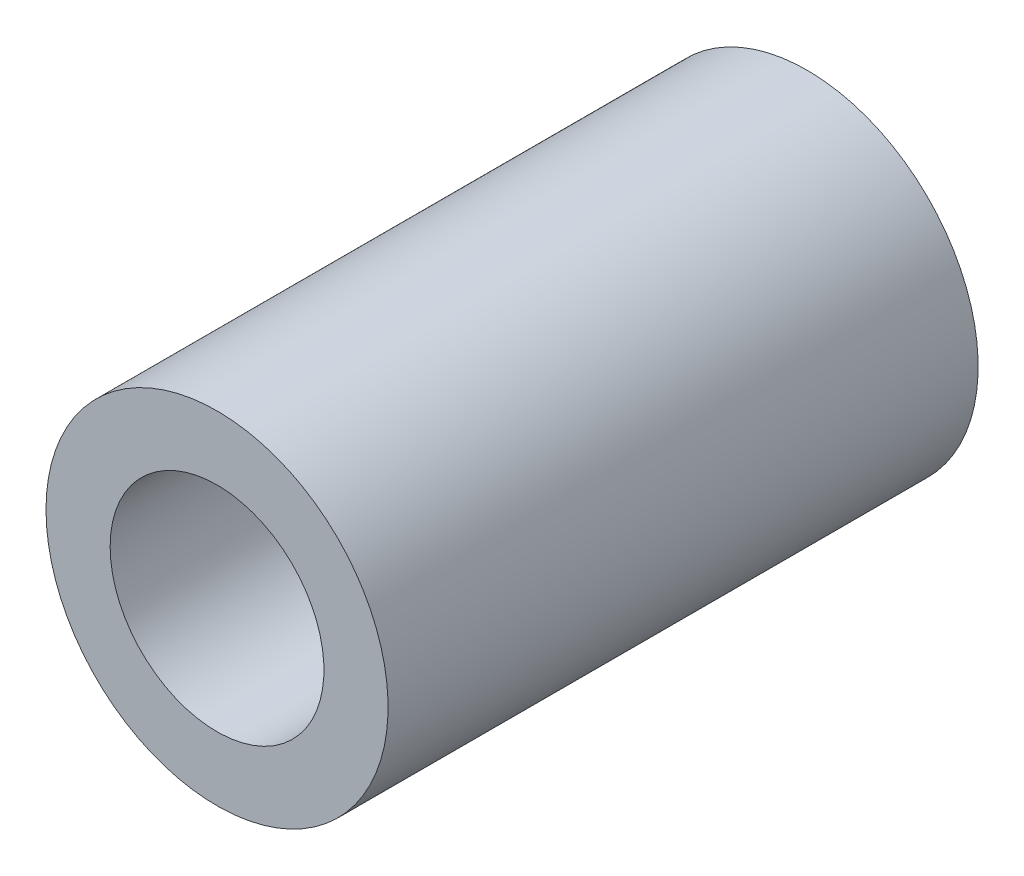
SolidWorks part; units mm, degrees
material "尼龙 101"
ref_plane "前视基准面" through (0, 0, 0) normal (0, 0, 1) x (1, 0, 0)
ref_plane "上视基准面" through (0, 0, 0) normal (0, 1, 0) x (1, 0, 0)
ref_plane "右视基准面" through (0, 0, 0) normal (1, 0, 0) x (0, 0, -1)
sketch "草图1" plane through (0, 0, 0) normal (0, 0, 1) x (1, 0, 0)
  circle A0 centre (0, 0) radius 2.5
  circle A1 centre (0, 0) radius 4
  dimension "D1" = 5
  dimension "D2" = 8
extrude "凸台-拉伸1" add sketch "草图1" along normal blind 13.8
